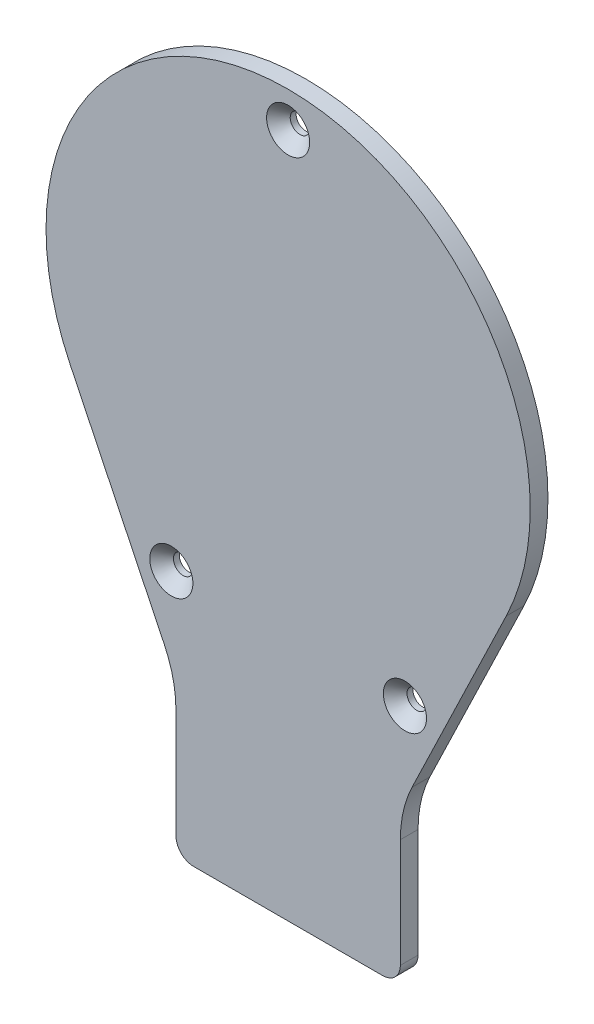
SolidWorks part; units mm, degrees
ref_plane "Plan de face" through (0, 0, 0) normal (0, 0, 1) x (1, 0, 0)
ref_plane "Plan de dessus" through (0, 0, 0) normal (0, 1, 0) x (1, 0, 0)
ref_plane "Plan de droite" through (0, 0, 0) normal (1, 0, 0) x (0, 0, -1)
sketch "Esquisse1" plane through (0, 0, 0) normal (0, 0, 1) x (1, 0, 0)
  line L5 (-16, 0) -> (16, 0)
  line L6 (19, 3) -> (19, 21.4305)
  line L7 (20.9844, 30.1161) -> (36.932, 63.1947)
  line L8 (-36.932, 63.1947) -> (-20.9844, 30.1161)
  line L9 (-19, 21.4305) -> (-19, 3)
  line L10 (-16, 0) -> (16, 0)
  line L11 (19, 3) -> (19, 21.4305)
  line L12 (20.9844, 30.1161) -> (36.932, 63.1947)
  line L13 (-36.932, 63.1947) -> (-20.9844, 30.1161)
  line L14 (-19, 21.4305) -> (-19, 3)
  circle A0 centre (-19.7801, 41.4343) radius 1.65 construction
  circle A1 centre (19.7801, 41.4343) radius 1.65 construction
  circle A2 centre (0, 116) radius 1.65 construction
  circle A3 centre (0, 116) radius 1.65
  circle A4 centre (19.7801, 41.4343) radius 1.65
  arc A5 (16, 0) -> (19, 3) centre (16, 3) ccw
  arc A6 (20.9844, 30.1161) -> (19, 21.4305) centre (39, 21.4305) ccw
  arc A7 (36.932, 63.1947) -> (-36.932, 63.1947) centre (0, 81) ccw
  arc A8 (-19, 21.4305) -> (-20.9844, 30.1161) centre (-39, 21.4305) ccw
  arc A9 (-19, 3) -> (-16, 0) centre (-16, 3) ccw
  arc A10 (16, 0) -> (19, 3) centre (16, 3) ccw
  arc A11 (20.9844, 30.1161) -> (19, 21.4305) centre (39, 21.4305) ccw
  arc A12 (36.932, 63.1947) -> (-36.932, 63.1947) centre (0, 81) ccw
  arc A13 (-19, 21.4305) -> (-20.9844, 30.1161) centre (-39, 21.4305) ccw
  arc A14 (-19, 3) -> (-16, 0) centre (-16, 3) ccw
  circle A15 centre (-19.7801, 41.4343) radius 1.65
  dimension "D1" = 0
extrude "Boss.-Extru.1" add sketch "Esquisse1" along normal blind 3
chamfer "Chanfrein1" distance 2 angle 45 3 edges at (21.4301, 41.4343, 3) (-18.1301, 41.4343, 3) (1.65, 116, 3)
